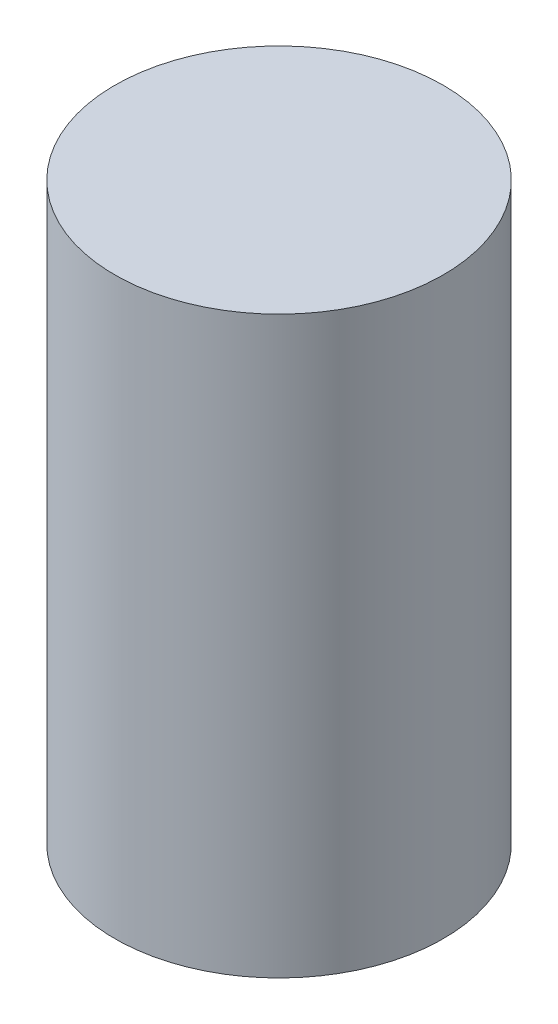
SolidWorks part; units mm, degrees
material "Plain Carbon Steel"
ref_plane "Front Plane" through (0, 0, 0) normal (0, 0, 1) x (1, 0, 0)
ref_plane "Top Plane" through (0, 0, 0) normal (0, 1, 0) x (1, 0, 0)
ref_plane "Right Plane" through (0, 0, 0) normal (1, 0, 0) x (0, 0, -1)
sketch "Sketch1" plane through (0, 0, 0) normal (0, 0, 1) x (1, 0, 0)
  line L0 (0, 0) -> (0, 70) construction
  line L1 (0, 0) -> (0, 35)
  line L2 (0, 35) -> (10, 35)
  line L3 (10, 35) -> (10, 0)
  line L4 (10, 0) -> (0, 0)
revolve "Revolve1" add sketch "Sketch1" angle 360 about L0
